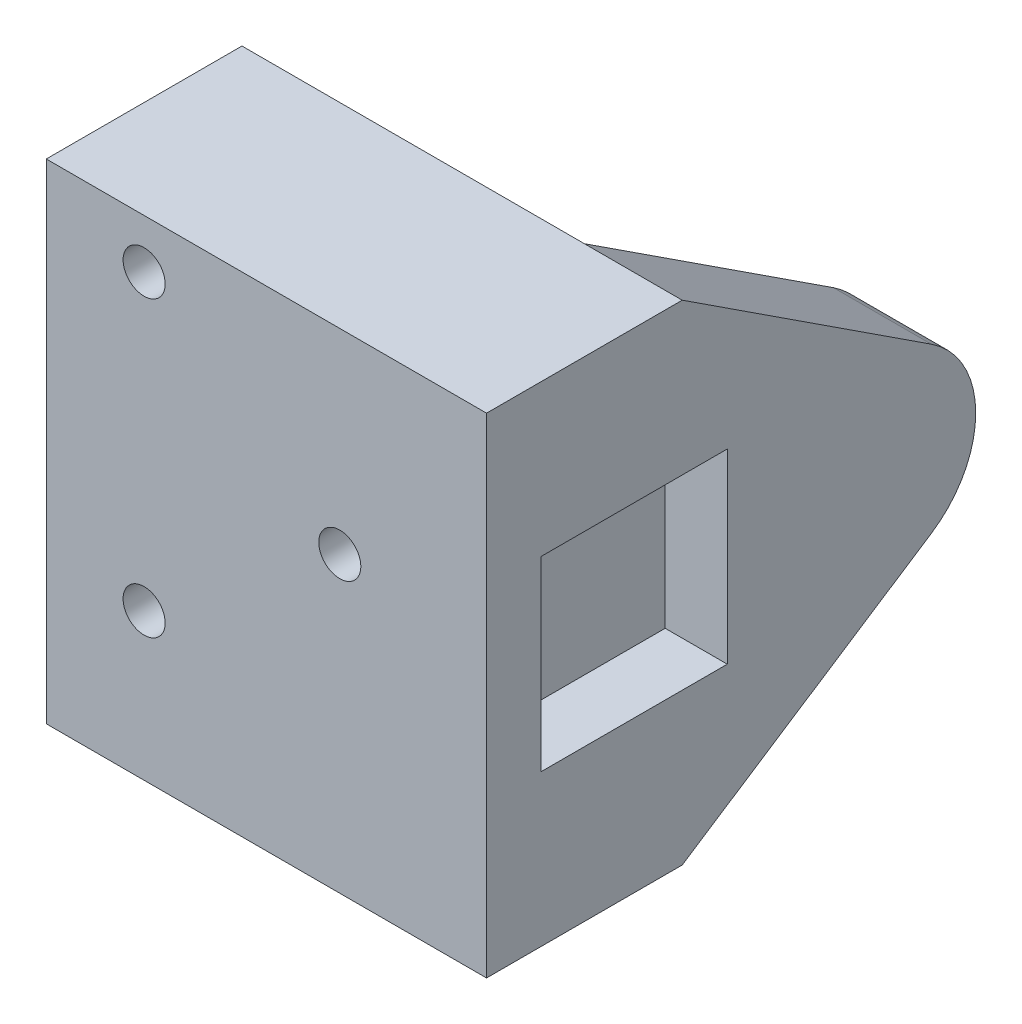
SolidWorks part; units mm, degrees
ref_plane "Front Plane" through (0, 0, 0) normal (0, 0, 1) x (1, 0, 0)
ref_plane "Top Plane" through (0, 0, 0) normal (0, 1, 0) x (1, 0, 0)
ref_plane "Right Plane" through (0, 0, 0) normal (1, 0, 0) x (0, 0, -1)
sketch "Sketch1" plane through (0, 0, 0) normal (1, 0, 0) x (0, 0, -1)
  line L0 (0, 25) -> (25.4668, 8.3734)
  line L1 (-20, -25) -> (0, -25)
  line L2 (-20, -25) -> (-20, 25)
  line L3 (-20, 25) -> (0, 25)
  line L4 (0, -25) -> (0, 25)
  line L5 (-10, 25) -> (-10, -25) construction
  line L6 (-20, 0) -> (0, 0) construction
  line L7 (25.4668, -8.3734) -> (0, -25)
  arc A0 (25.4668, 8.3734) -> (25.4668, -8.3734) centre (20, 0) cw
  point P0 (-10, 0)
  dimension "D3" = 10
  dimension "D4" = 50
  dimension "D1" = 50
  dimension "D2" = 20
extrude "Boss-Extrude1" add sketch "Sketch1" along normal blind 10 contours L1 L4 L3 L2 | A0 L0 L4 L7
hole_wizard "CBORE for M5 SBHCS1" positions "Sketch3" profile "Sketch4" counterbore size "M5" standard "ANSI Metric"
sketch "Sketch3" plane through (12.7, 0, 0) normal (1, 0, 0) x (0, 0, -1)
  line L0 (-10, 17.5) -> (-10, -17.5) construction
  line L3 (-10, 0) -> (0, 0) construction
  line L6 (-10, 25) -> (-10, 17.5) construction
  line L7 (-20, 25) -> (0, 25) construction
  point P0 (-10, 17.5)
  point P2 (-10, -17.5)
  dimension "D1" = 35
sketch "Sketch4" plane through (12.7, 17.5, 10) normal (0, 1, 0) x (0, 0, -1)
  line L0 (0, 0) -> (0, 12.7)
  line L1 (0, 12.7) -> (2.75, 12.7)
  line L3 (2.75, 12.7) -> (2.75, 2.75)
  line L4 (2.75, 2.75) -> (5.25, 2.75)
  line L5 (5.25, 2.75) -> (5.25, 0)
  line L7 (5.25, 0) -> (0, 0)
  line L11 (0, -6.35) -> (0, 107.95) construction
  dimension "Thru Hole Dia." = 5.5
  dimension "Thru Hole Depth" = 12.7
  dimension "C'Bore Dia." = 10.5
  dimension "C'Bore Depth" = 2.75
sketch "Sketch5" plane through (10, 0, 0) normal (1, 0, 0) x (0, 0, -1)
  line L1 (-14.4406, 9.525) -> (4.6094, 9.525)
  line L2 (-14.4406, 9.525) -> (-14.4406, -9.525)
  line L3 (-14.4406, -9.525) -> (4.6094, -9.525)
  line L4 (4.6094, 9.525) -> (4.6094, -9.525)
  line L5 (-4.9156, -9.525) -> (-4.9156, 9.525) construction
  line L6 (-14.4406, 0) -> (4.6094, 0) construction
  point P168 (-4.9156, 0)
  dimension "D1" = 19.05
extrude "Cut-Extrude1" cut sketch "Sketch5" against normal blind 6.35
sketch "Sketch7" plane through (0, 0, 0) normal (-1, 0, 0) x (0, 0, 1)
  line L1 (0, 25) -> (20, 25)
  line L2 (0, 25) -> (0, -25)
  line L3 (0, -25) -> (20, -25)
  line L4 (20, 25) -> (20, -25)
  line L5 (10, -25) -> (10, 25) construction
  line L6 (0, 0) -> (20, 0) construction
  point P144 (10, 0)
extrude "Boss-Extrude2" add sketch "Sketch7" along normal blind 35
hole_wizard "M4 Clearance Hole1" positions "Sketch8" profile "Sketch9" hole size "M4" standard "ANSI Metric" end condition through all
sketch "Sketch8" plane through (0, 0, 20) normal (0, 0, 1) x (1, 0, 0)
  line L0 (-25, 20) -> (-25, -10) construction
  line L3 (-5, 5) -> (-25, 5) construction
  line L8 (-35, -25) -> (-35, 25) construction
  line L9 (10, 25) -> (-35, 25) construction
  point P0 (-25, 20)
  point P2 (-25, -10)
  point P4 (-5, 5)
  point P26 (0, 0)
  point P27 (4.346, 2.1729)
  dimension "D1" = 30
  dimension "D2" = 10
  dimension "D3" = 20
  dimension "D4" = 20
sketch "Sketch9" plane through (-25, 20, 20) normal (1, 0, 0) x (0, -1, 0)
  line L0 (0, 0) -> (0, 50)
  line L1 (0, 50) -> (2.15, 50)
  line L2 (2.15, 50) -> (2.15, 0)
  line L5 (2.15, 0) -> (0, 0)
  line L11 (0, -6.35) -> (0, 107.95) construction
  dimension "Thru Hole Dia." = 4.3
  dimension "Thru Hole Depth" = 50
